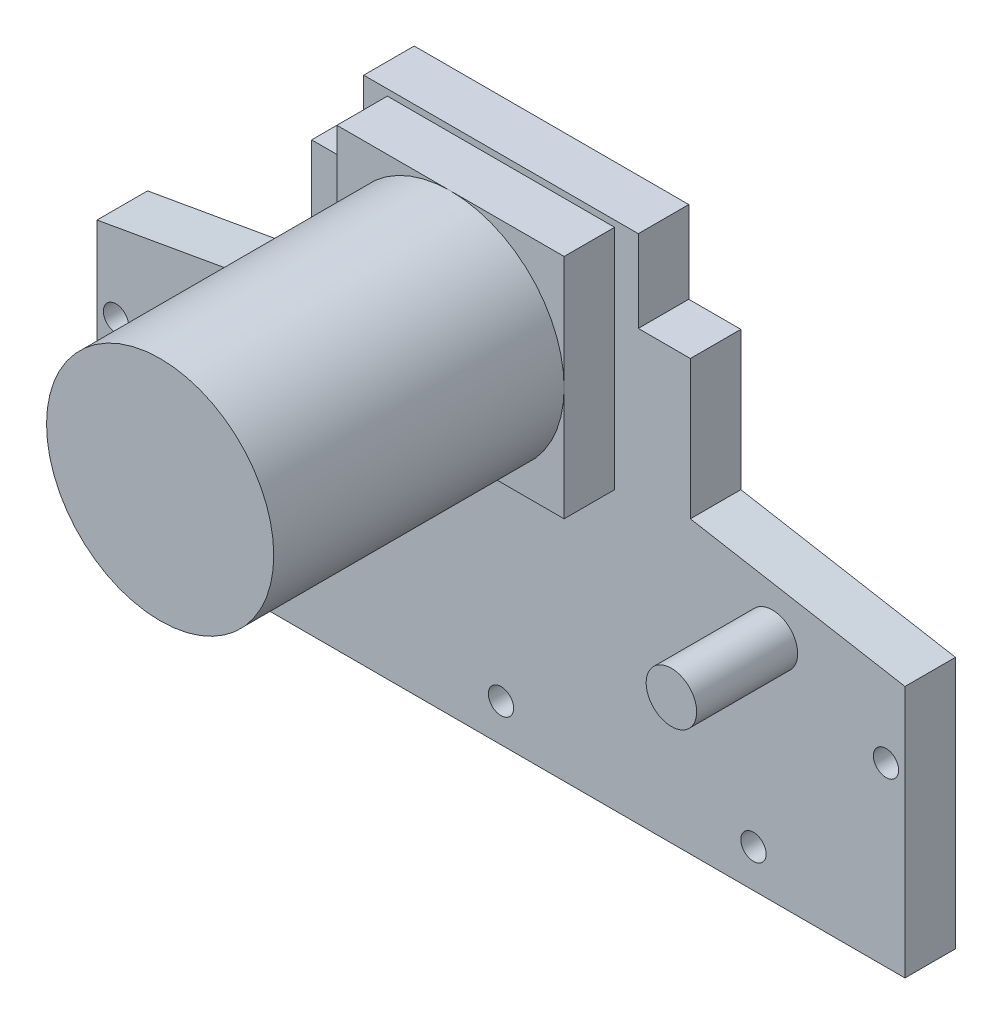
SolidWorks part; units mm, degrees
material "Nickel"
ref_plane "Front Plane" through (0, 0, 0) normal (0, 0, 1) x (1, 0, 0)
ref_plane "Top Plane" through (0, 0, 0) normal (0, 1, 0) x (1, 0, 0)
ref_plane "Right Plane" through (0, 0, 0) normal (1, 0, 0) x (0, 0, -1)
sketch "Sketch1" plane through (0, 0, 0) normal (0, 0, 1) x (1, 0, 0)
  line L0 (-32, 0) -> (32, 0)
  line L1 (-1015.4659, 23) -> (48984.5341, 23) construction
  line L2 (-15, 23) -> (15, 23)
  line L3 (-32, 0) -> (-32, 20)
  line L4 (-32, 20) -> (-15, 23)
  line L5 (32, 0) -> (32, 20)
  line L6 (32, 20) -> (15, 23)
  line L7 (-15, 23) -> (-15, 34)
  line L8 (-15, 34) -> (15, 34)
  line L9 (15, 34) -> (15, 23)
  line L10 (-1006.9308, 40.5) -> (48993.0692, 40.5) construction
  line L11 (-10.875, 40.5) -> (10.875, 40.5)
  line L12 (-10.875, 40.5) -> (-10.875, 34)
  line L13 (10.875, 40.5) -> (10.875, 34)
  line L14 (0, 34) -> (0, 40.5) construction
  dimension "D1" = 64
  dimension "D2" = 23
  dimension "D3" = 30
  dimension "D4" = 20
  dimension "D5" = 11
  dimension "D6" = 6.5
  dimension "D7" = 21.75
extrude "Boss-Extrude1" add sketch "Sketch1" along normal blind 4 contours L5 L6 L2 L4 L3 L0 | L9 L8 L7 L2 | L13 L11 L12 L8
sketch "Sketch2" plane through (0, 0, 4) normal (0, 0, 1) x (1, 0, 0)
  line L0 (-1024.4669, 3) -> (48975.5331, 3) construction
  line L1 (-32, 0) -> (32, 0) construction
  line L2 (-20, 3) -> (20, 3)
  line L3 (-32, 0) -> (-32, 20) construction
  line L4 (0, -997) -> (0, 49003) construction
  circle A0 centre (-20, 3) radius 1
  circle A1 centre (20, 3) radius 1
  circle A2 centre (0, 3) radius 1
  circle A3 centre (-30.5, 14) radius 1
  circle A4 centre (30.5, 14) radius 1
  dimension "D3" = 2
  dimension "D1" = 40
  dimension "D2" = 3
  dimension "D5" = 14
  dimension "D6" = 1.5
extrude "Cut-Extrude1" cut sketch "Sketch2" against normal blind 5
sketch "Sketch3" plane through (0, 0, 4) normal (0, 0, 1) x (1, 0, 0)
  line L0 (0, 40.5) -> (0, 0) construction
  line L1 (-10.875, 40.5) -> (10.875, 40.5) construction
  line L2 (-32, 0) -> (32, 0) construction
  line L4 (-8.5, 39.5) -> (8.5, 39.5)
  line L5 (-8.5, 39.5) -> (-8.5, 22.5)
  line L6 (-8.5, 22.5) -> (8.5, 22.5)
  line L7 (8.5, 39.5) -> (8.5, 22.5)
  circle A0 centre (0, 31) radius 9
  circle A1 centre (0, 31) radius 8.5
  dimension "D1" = 18
  dimension "D2" = 17
  dimension "D3" = 17
  dimension "D4" = 1
extrude "Boss-Extrude2" add sketch "Sketch3" along normal blind 27 contours A0
sketch "Sketch4" plane through (0, 0, 31) normal (0, 0, 1) x (1, 0, 0)
  circle A0 centre (0, 31) radius 9
sketch "Sketch5" plane through (0, 0, 0) normal (0, 0, -1) x (-1, 0, 0)
  line L0 (32, 0) -> (-32, 0) construction
  line L1 (-5, 10) -> (13, 10)
  line L2 (-5, 10) -> (-5, 28)
  line L3 (-5, 28) -> (13, 28)
  line L4 (13, 10) -> (13, 28)
  line L5 (32, 0) -> (32, 20) construction
  line L6 (15, 23) -> (15, 34) construction
  dimension "D1" = 28
  dimension "D2" = 19
  dimension "D3" = 20
  dimension "D4" = 10
extrude "Boss-Extrude3" add sketch "Sketch5" along normal blind 3
sketch "Sketch6" plane through (0, 0, 4) normal (0, 0, 1) x (1, 0, 0)
  line L0 (21.5, 18) -> (-21.5, 18) construction
  line L1 (0, 0) -> (0, 18) construction
  line L2 (-32, 0) -> (32, 0) construction
  circle A0 centre (21.5, 18) radius 2
  circle A1 centre (-21.5, 18) radius 2
  dimension "D2" = 4
  dimension "D1" = 43
  dimension "D3" = 18
extrude "Boss-Extrude4" add sketch "Sketch6" along normal blind 8
sketch "Sketch7" plane through (0, 0, 4) normal (0, 0, 1) x (1, 0, 0)
  line L1 (-9, 40) -> (9, 40)
  line L2 (-9, 40) -> (-9, 22)
  line L3 (-9, 22) -> (9, 22)
  line L4 (9, 40) -> (9, 22)
  line L5 (-9, 40) -> (9, 22) construction
  line L6 (-9, 22) -> (9, 40) construction
  circle A0 centre (0, 31) radius 9 construction
  circle A1 centre (0, 31) radius 9 construction
  point P0 (0, 31)
extrude "Boss-Extrude5" add sketch "Sketch7" along normal blind 4
